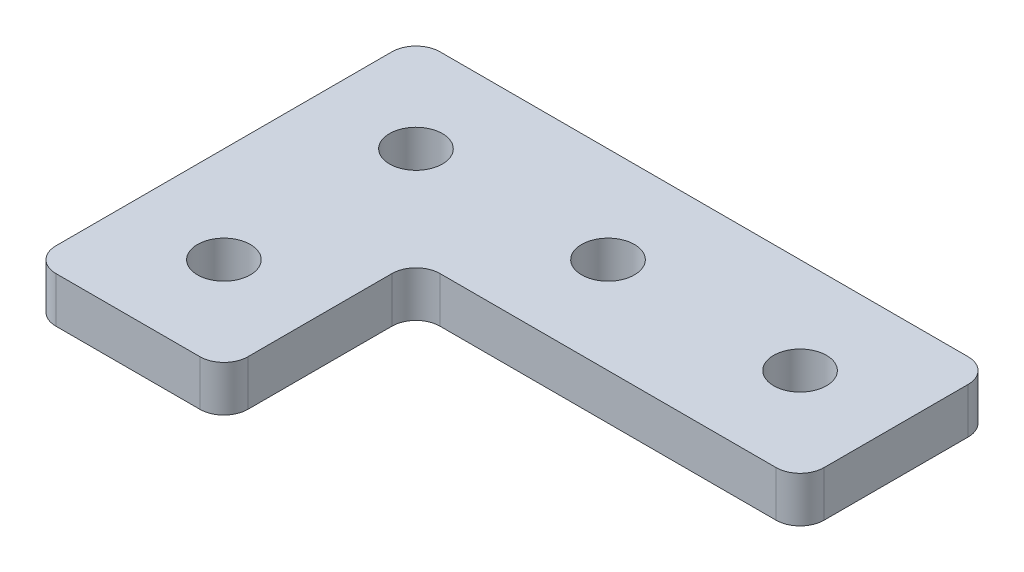
SolidWorks part; units mm, degrees
material "6061-T6 (SS)"
ref_plane "Front Plane" through (0, 0, 0) normal (0, 0, 1) x (1, 0, 0)
ref_plane "Top Plane" through (0, 0, 0) normal (0, 1, 0) x (1, 0, 0)
ref_plane "Right Plane" through (0, 0, 0) normal (1, 0, 0) x (0, 0, -1)
sketch "Sketch1" plane through (0, 0, 0) normal (0, 1, 0) x (1, 0, 0)
  line L0 (-10, 7.5) -> (-10, -27.5)
  line L1 (-7.5, -30) -> (7.5, -30)
  line L2 (10, -27.5) -> (10, -12.5)
  line L3 (12.5, -10) -> (47.5, -10)
  line L4 (50, -7.5) -> (50, 7.5)
  line L5 (47.5, 10) -> (-7.5, 10)
  line L6 (0, -30) -> (0, 10) construction
  line L7 (50, 0) -> (-10, 0) construction
  circle A0 centre (0, 0) radius 2.75
  circle A1 centre (20, 0) radius 2.75
  circle A2 centre (40, 0) radius 2.75
  circle A3 centre (20, -20) radius 2.75 [skipped]
  circle A4 centre (40, -20) radius 2.75 [skipped]
  circle A5 centre (0, -20) radius 2.75
  arc A6 (50, 7.5) -> (47.5, 10) centre (47.5, 7.5) ccw
  arc A7 (47.5, -10) -> (50, -7.5) centre (47.5, -7.5) ccw
  arc A8 (7.5, -30) -> (10, -27.5) centre (7.5, -27.5) ccw
  arc A9 (-10, -27.5) -> (-7.5, -30) centre (-7.5, -27.5) ccw
  arc A10 (10, -12.5) -> (12.5, -10) centre (12.5, -12.5) cw
  arc A11 (-10, 7.5) -> (-7.5, 10) centre (-7.5, 7.5) cw
  point P28 (50, -10)
  point P31 (10, -30)
  point P34 (-10, -30)
  point P37 (10, -10)
  point P40 (-10, 10)
  dimension "D6" = 5.5
  dimension "D9" = 2.5
  dimension "D1" = 20
  dimension "D2" = 40
  dimension "D3" = 40
  dimension "D7" = 20
  dimension "D8" = 20
  dimension "D4" = 3
  dimension "D5" = 2
extrude "Boss-Extrude1" add sketch "Sketch1" along normal mid plane 4.7498
